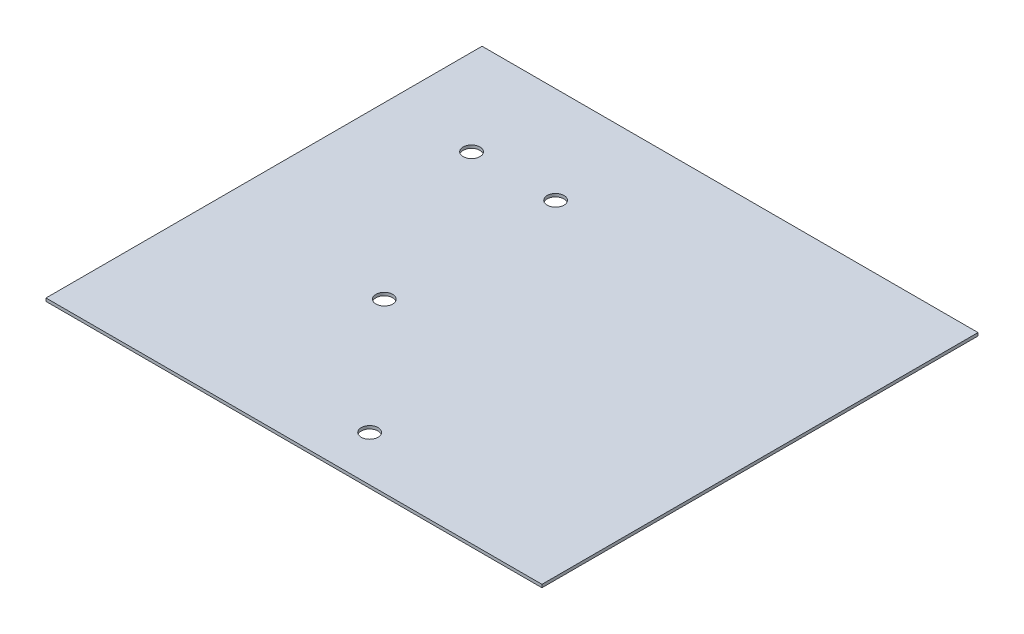
SolidWorks part; units mm, degrees
material "1060 Alloy"
ref_plane "Front Plane" through (0, 0, 0) normal (0, 0, 1) x (1, 0, 0)
ref_plane "Top Plane" through (0, 0, 0) normal (0, 1, 0) x (1, 0, 0)
ref_plane "Right Plane" through (0, 0, 0) normal (1, 0, 0) x (0, 0, -1)
sketch "Sketch1" plane through (0, 0, 0) normal (0, 1, 0) x (1, 0, 0)
  line L1 (0, 0) -> (149.86, 0)
  line L2 (0, 0) -> (0, 131.7625)
  line L3 (0, 131.7625) -> (149.86, 131.7625)
  line L4 (149.86, 0) -> (149.86, 131.7625)
  circle A0 centre (51.435, 50.8) radius 2.54
  circle A1 centre (26.035, 102.5525) radius 2.54
  circle A2 centre (51.435, 102.5525) radius 2.54
  circle A3 centre (84.074, 13.716) radius 2.54
  dimension "D3" = 5.08
  dimension "D4" = 5.08
  dimension "D5" = 5.08
  dimension "D6" = 5.08
  dimension "D7" = 50.8
  dimension "D8" = 51.435
  dimension "D9" = 84.074
  dimension "D10" = 13.716
  dimension "D12" = 51.435
  dimension "D13" = 29.21
  dimension "D14" = 29.21
  dimension "D1" = 149.86
  dimension "D2" = 131.7625
  dimension "D11" = 26.035
extrude "Boss-Extrude1" add sketch "Sketch1" along normal blind 0.9119
